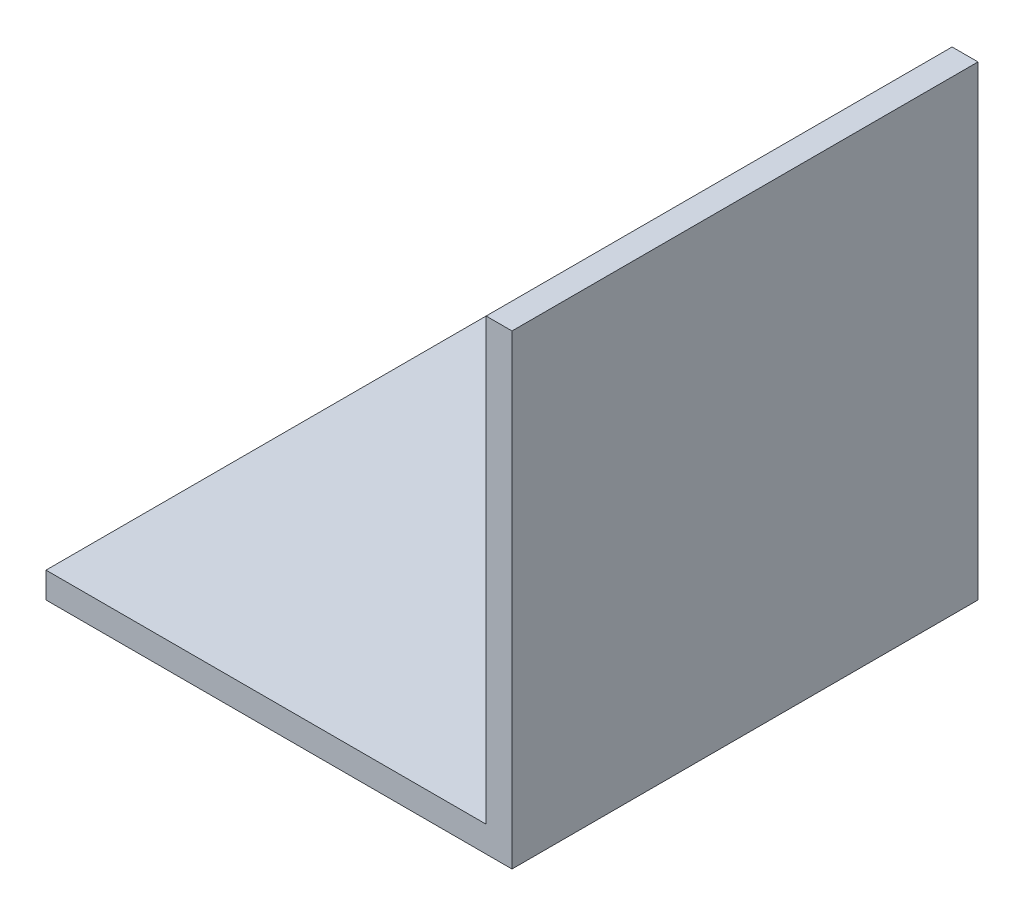
SolidWorks part; units mm, degrees
ref_plane "Front Plane" through (0, 0, 0) normal (0, 0, 1) x (1, 0, 0)
ref_plane "Top Plane" through (0, 0, 0) normal (0, 1, 0) x (1, 0, 0)
ref_plane "Right Plane" through (0, 0, 0) normal (1, 0, 0) x (0, 0, -1)
sketch "Sketch2" plane through (0, 0, 0) normal (0, 1, 0) x (1, 0, 0)
  line L1 (0, 0) -> (-457.2, 0)
  line L2 (0, 0) -> (0, 457.2)
  line L3 (0, 457.2) -> (-457.2, 457.2)
  line L4 (-457.2, 0) -> (-457.2, 457.2)
  dimension "D1" = 457.2
  dimension "D2" = 457.2
extrude "Boss-Extrude1" add sketch "Sketch2" along normal blind 25.4
sketch "Sketch3" plane through (0, 25.4, 0) normal (0, 1, 0) x (1, 0, 0)
  line L0 (0, 457.2) -> (-457.2, 457.2) construction
  line L1 (-25.4, 457.2) -> (0, 457.2)
  line L2 (-25.4, 457.2) -> (-25.4, 0)
  line L3 (-25.4, 0) -> (0, 0)
  line L4 (0, 457.2) -> (0, 0)
  dimension "D1" = 25.4
extrude "Boss-Extrude2" add sketch "Sketch3" along normal blind 431.8
